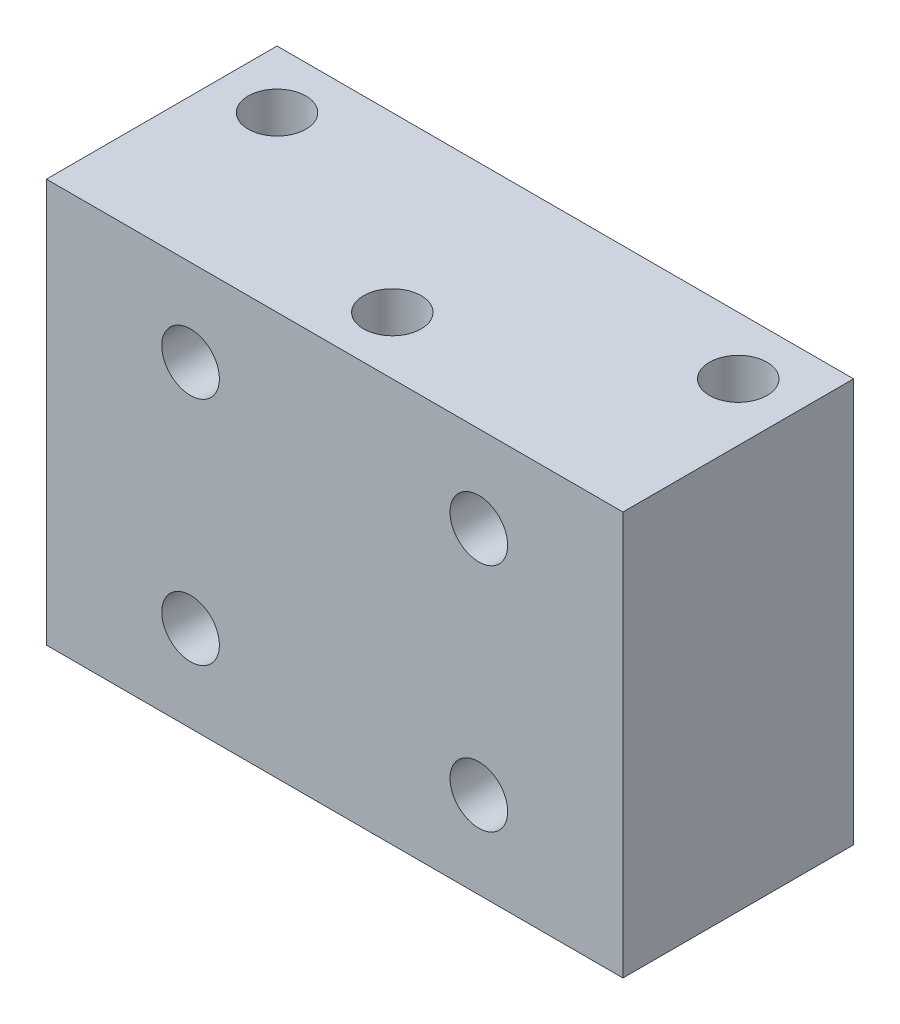
SolidWorks part; units mm, degrees
ref_plane "Front Plane" through (0, 0, 0) normal (0, 0, 1) x (1, 0, 0)
ref_plane "Top Plane" through (0, 0, 0) normal (0, 1, 0) x (1, 0, 0)
ref_plane "Right Plane" through (0, 0, 0) normal (1, 0, 0) x (0, 0, -1)
sketch "Sketch1" plane through (0, 0, 0) normal (0, 0, 1) x (1, 0, 0)
  line L1 (-127, -88.9) -> (127, -88.9)
  line L2 (-127, -88.9) -> (-127, 88.9)
  line L3 (-127, 88.9) -> (127, 88.9)
  line L4 (127, -88.9) -> (127, 88.9)
  line L5 (-127, -88.9) -> (127, 88.9) construction
  line L6 (-127, 88.9) -> (127, -88.9) construction
  point P0 (0, 0)
  dimension "D1" = 177.8
  dimension "D2" = 254
extrude "Boss-Extrude1" add sketch "Sketch1" along normal blind 101.6
sketch "Sketch4" plane through (0, -88.9, 0) normal (0, -1, 0) x (1, 0, 0)
  line L1 (127, 101.6) -> (127, 0) construction
  line L2 (-127, 101.6) -> (-127, 0) construction
  line L4 (-127, 0) -> (127, 0) construction
  circle A0 centre (-101.6, 25.4) radius 12.7
  circle A1 centre (101.6, 25.4) radius 12.7
  point P6 (-124.1312, 18.091)
  point P9 (83.2, 19.4595)
  point P12 (-102.2349, 0)
  dimension "D1" = 203.2
  dimension "D2" = 25.4
  dimension "D3" = 25.4
  dimension "D4" = 25.4
extrude "Cut-Extrude3" cut sketch "Sketch4" against normal blind 50.8
mirror "Mirror4" about plane through (0, 0, 0) normal (0, 1, 0) of "Cut-Extrude3"
sketch "Sketch6" plane through (0, -88.9, 0) normal (0, -1, 0) x (1, 0, 0)
  line L0 (-127, 101.6) -> (127, 101.6) construction
  circle A0 centre (0, 76.2) radius 12.7
  dimension "D1" = 25.4
extrude "Cut-Extrude4" cut sketch "Sketch6" against normal blind 50.8
mirror "Mirror5" about plane through (0, 0, 0) normal (0, 1, 0) of "Cut-Extrude4"
sketch "Sketch7" plane through (0, 0, 101.6) normal (0, 0, 1) x (1, 0, 0)
  line L0 (-127, -88.9) -> (127, -88.9) construction
  line L3 (127, -88.9) -> (127, 88.9) construction
  circle A0 centre (63.5, -50.8) radius 12.7
  circle A1 centre (63.5, 50.8) radius 12.7
  circle A2 centre (-63.5, -50.8) radius 12.7
  circle A4 centre (-63.5, 50.8) radius 12.7
  point P10 (0, 0)
  point P13 (-240.7401, -113.637)
  dimension "D4" = 101.6
  dimension "D5" = 25.4
  dimension "D6" = 25.4
  dimension "D7" = 25.4
  dimension "D8" = 38.1
  dimension "D2" = 25.4
  dimension "D1" = 101.6
  dimension "D3" = 38.1
  dimension "D9" = 127
  dimension "D10" = 63.5
extrude "Cut-Extrude5" cut sketch "Sketch7" against normal blind 33.02
